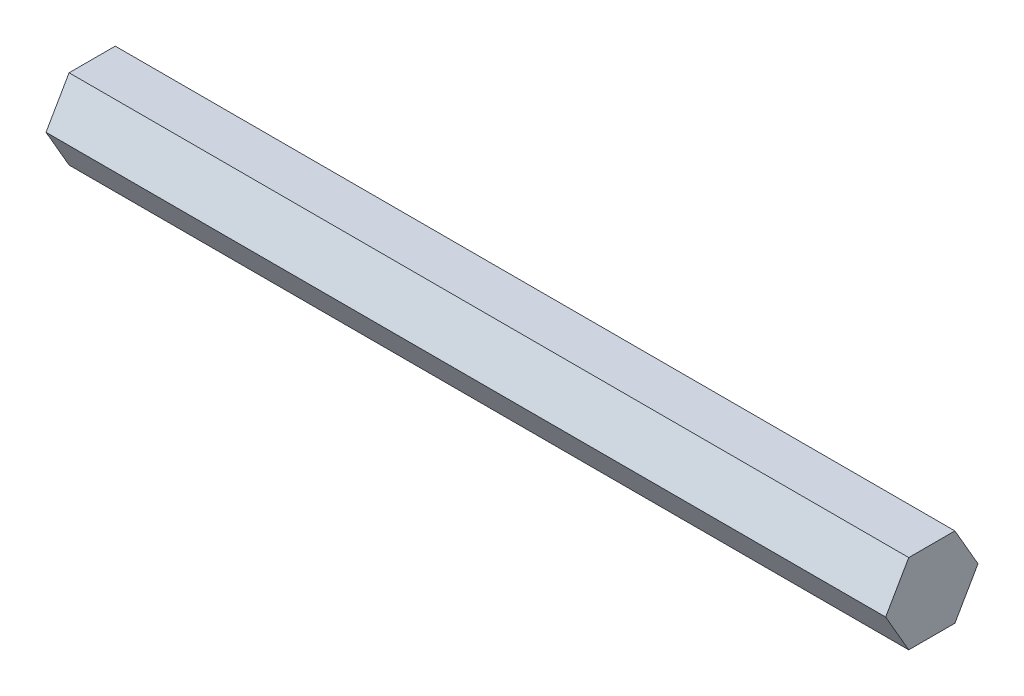
SolidWorks part; units mm, degrees
ref_plane "Front Plane" through (0, 0, 0) normal (0, 0, 1) x (1, 0, 0)
ref_plane "Top Plane" through (0, 0, 0) normal (0, 1, 0) x (1, 0, 0)
ref_plane "Right Plane" through (0, 0, 0) normal (1, 0, 0) x (0, 0, -1)
sketch "Sketch1" plane through (0, 0, 0) normal (1, 0, 0) x (0, 0, -1)
  line L1 (7.3323, 0) -> (3.6662, 6.35)
  line L2 (3.6662, 6.35) -> (-3.6662, 6.35)
  line L3 (-3.6662, 6.35) -> (-7.3323, 0)
  line L4 (-7.3323, 0) -> (-3.6662, -6.35)
  line L5 (-3.6662, -6.35) -> (3.6662, -6.35)
  line L6 (3.6662, -6.35) -> (7.3323, 0)
  circle A0 centre (0, 0) radius 6.35 construction
  dimension "D1" = 12.7
extrude "Boss-Extrude1" add sketch "Sketch1" along normal blind 133.35
